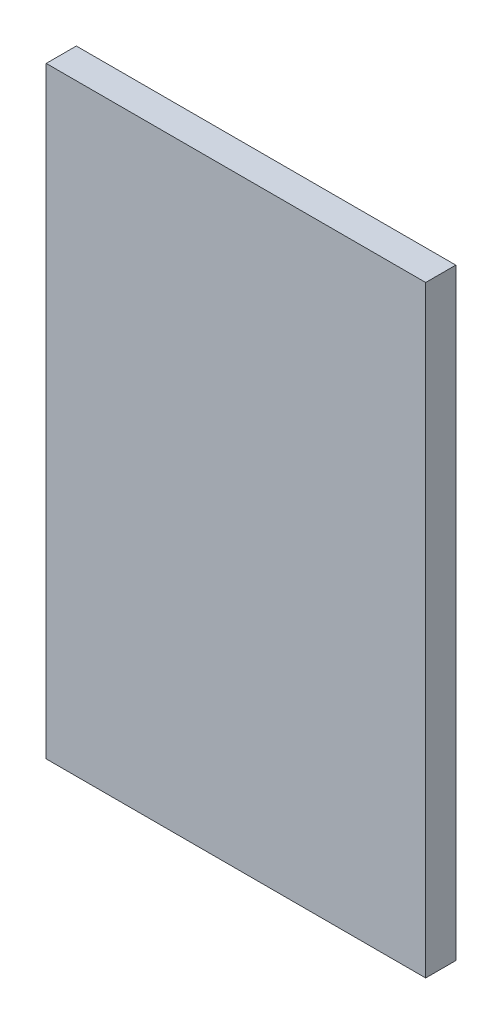
SolidWorks part; units mm, degrees
ref_plane "Piano frontale" through (0, 0, 0) normal (0, 0, 1) x (1, 0, 0)
ref_plane "Piano superiore" through (0, 0, 0) normal (0, 1, 0) x (1, 0, 0)
ref_plane "Piano destro" through (0, 0, 0) normal (1, 0, 0) x (0, 0, -1)
sketch "Schizzo1" plane through (0, 0, 0) normal (0, 0, 1) x (1, 0, 0)
  line L1 (126, -200) -> (-126, -200)
  line L2 (126, -200) -> (126, 200)
  line L3 (126, 200) -> (-126, 200)
  line L4 (-126, -200) -> (-126, 200)
  line L5 (126, -200) -> (-126, 200) construction
  line L6 (126, 200) -> (-126, -200) construction
  point P0 (0, 0)
  dimension "D1" = 252
  dimension "D2" = 400
extrude "Estrusione-Estrusione1" add sketch "Schizzo1" along normal blind 20
sketch "Schizzo2" plane through (0, 0, 20) normal (0, 0, 1) x (1, 0, 0)
  line L0 (1290.7582, 59.0012) -> (-670.2418, 59.0012) construction
  line L1 (1290.7582, 51.1433) -> (-670.2418, 51.1433) construction
  line L2 (1290.7582, 91.1433) -> (-670.2418, 91.1433) construction
  line L3 (1290.7582, 99.0012) -> (-670.2418, 99.0012) construction
  line L4 (-126, 200) -> (-126, -200)
  line L5 (-126, -200) -> (126, -200)
  line L6 (126, -200) -> (126, 200)
  line L7 (126, 200) -> (-126, 200)
  line L8 (-126, 200) -> (-126, -200) construction
  line L9 (-126, -200) -> (126, -200) construction
  line L10 (126, -200) -> (126, 200) construction
  line L11 (126, 200) -> (-126, 200) construction
  line L12 (1290.7582, 59.0012) -> (-670.2418, 59.0012) construction
  line L13 (1290.7582, 51.1433) -> (-670.2418, 51.1433) construction
  line L14 (1290.7582, 91.1433) -> (-670.2418, 91.1433) construction
  line L15 (1290.7582, 99.0012) -> (-670.2418, 99.0012) construction
  line L16 (126, -7.4278) -> (-126, -7.4278) construction
  line L17 (126, 12.5722) -> (-126, 12.5722) construction
  line L18 (126, -7.4278) -> (-126, -7.4278) construction
  line L19 (126, 12.5722) -> (-126, 12.5722) construction
  line L20 (-126, -7.4278) -> (-126, 12.5722) construction
  line L21 (126, 2.5722) -> (-126, 2.5722) construction
  line L22 (-126, -7.4278) -> (126, -7.4278) construction
  line L23 (-126, -7.4278) -> (-126, 12.5722) construction
  line L24 (-126, 12.5722) -> (126, 12.5722) construction
  line L25 (126, -7.4278) -> (126, 12.5722) construction
  circle A0 centre (110, 55.0722) radius 3.9289
  circle A1 centre (110, 95.0722) radius 3.9289
  circle A2 centre (-110, 55.0722) radius 3.9289
  circle A3 centre (-110, 95.0722) radius 3.9289
  circle A4 centre (110, 2.5722) radius 3.5
  circle A5 centre (-110, 2.5722) radius 3.5
  circle A6 centre (55, 2.5722) radius 3.5
  circle A8 centre (-55, 2.5722) radius 3.5
  circle A9 centre (20, 2.5722) radius 3.5
  circle A10 centre (-20, 2.5722) radius 3.5
  circle A11 centre (165, 2.5722) radius 3.5 [skipped]
  dimension "D2" = 16
  dimension "D3" = 7.8579
  dimension "D4" = 16
  dimension "D5" = 7.8579
  dimension "D6" = 7
  dimension "D7" = 7
  dimension "D8" = 2
  dimension "D1" = 0
  dimension "D9" = 2
  dimension "D10" = 2
  dimension "D11" = 2
